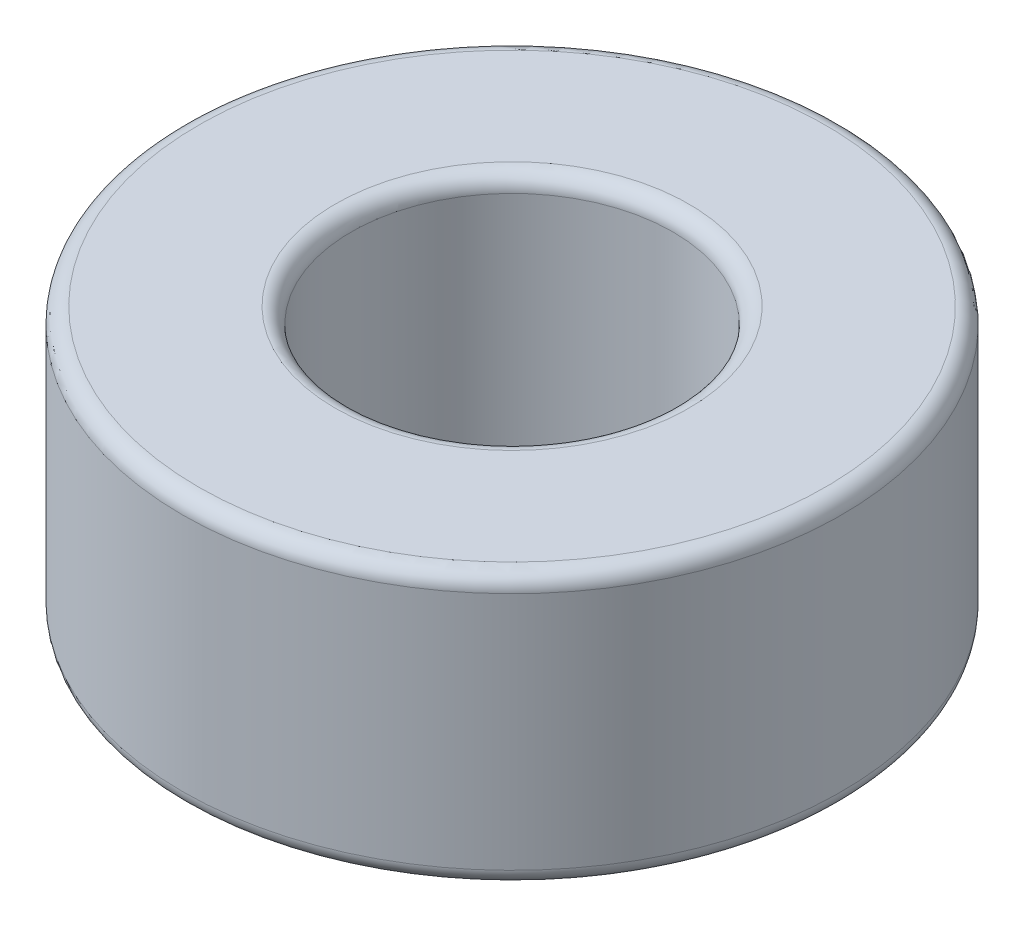
SolidWorks part; units mm, degrees
ref_plane "Front Plane" through (0, 0, 0) normal (0, 0, 1) x (1, 0, 0)
ref_plane "Top Plane" through (0, 0, 0) normal (0, 1, 0) x (1, 0, 0)
ref_plane "Right Plane" through (0, 0, 0) normal (1, 0, 0) x (0, 0, -1)
sketch "Sketch1" plane through (0, 0, 0) normal (0, 1, 0) x (1, 0, 0)
  circle A0 centre (0, 0) radius 20.5
  circle A1 centre (0, 0) radius 10
  dimension "D1" = 41
  dimension "D2" = 20
extrude "Boss-Extrude1" add sketch "Sketch1" along normal blind 16.9
fillet "Fillet1" radius 1 4 edges at (0, 0, 10) (0, 0, 20.5) (0, 16.9, 10) (0, 16.9, 20.5)
